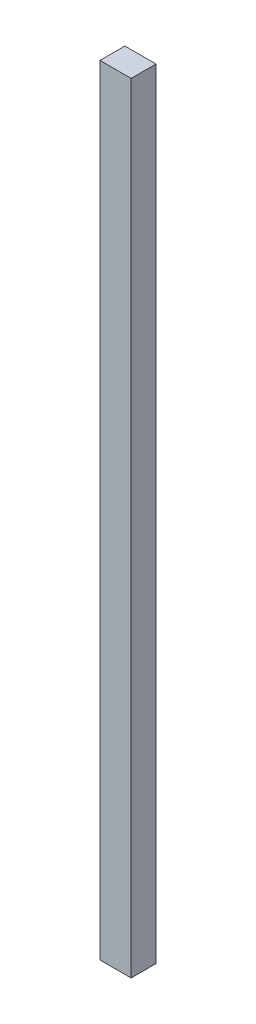
SolidWorks part; units mm, degrees
ref_plane "Front Plane" through (0, 0, 0) normal (0, 0, 1) x (1, 0, 0)
ref_plane "Top Plane" through (0, 0, 0) normal (0, 1, 0) x (1, 0, 0)
ref_plane "Right Plane" through (0, 0, 0) normal (1, 0, 0) x (0, 0, -1)
sketch "Sketch1" plane through (0, 0, 0) normal (0, 0, 1) x (1, 0, 0)
  line L0 (1780, -200) -> (1780, -1450)
  line L1 (1780, -1450) -> (1830, -1450)
  line L2 (1830, -1450) -> (1830, -200)
  line L3 (1830, -200) -> (1780, -200)
extrude "Boss-Extrude1" add sketch "Sketch1" along normal blind 40
